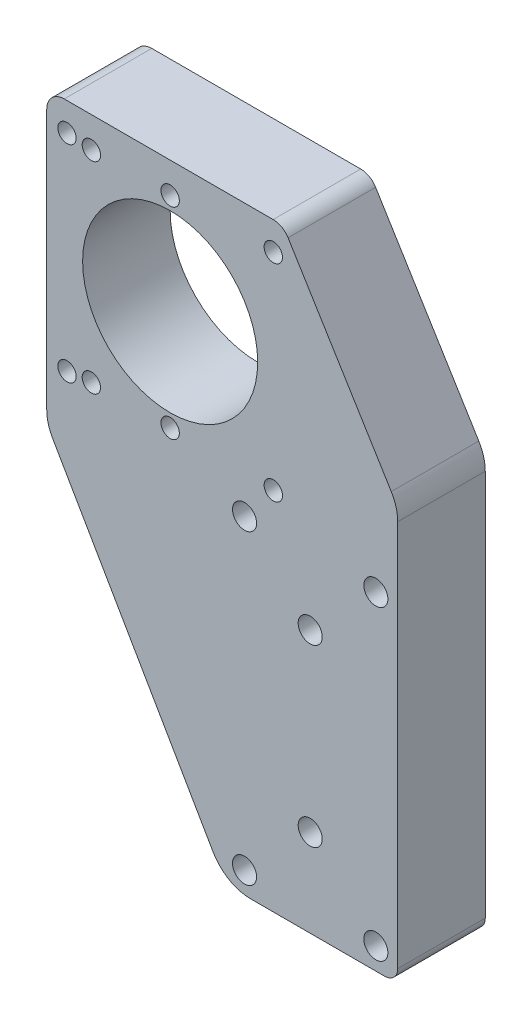
SolidWorks part; units mm, degrees
ref_plane "Front Plane" through (0, 0, 0) normal (0, 0, 1) x (1, 0, 0)
ref_plane "Top Plane" through (0, 0, 0) normal (0, 1, 0) x (1, 0, 0)
ref_plane "Right Plane" through (0, 0, 0) normal (1, 0, 0) x (0, 0, -1)
sketch "Sketch1" plane through (0, 0, 0) normal (0, 0, 1) x (1, 0, 0)
  line L0 (-130, 510) -> (13.8884, 510) construction
  line L1 (-170.2, 540.8246) -> (-129.3094, 470)
  line L2 (-116.2253, 607) -> (-90, 564.2553)
  line L15 (-90, 473) -> (-90, 564.2553)
  line L16 (-90, 473) -> (-90, 547) construction
  line L24 (-170.2, 540.8246) -> (-170.2, 607)
  line L25 (-170.2, 607) -> (-116.2253, 607)
  line L183 (-129.3094, 470) -> (-93, 470)
  arc A1 (-113.8, 602.2) -> (-116.8, 605.2) centre (-116.8, 602.2) ccw construction
  arc A13 (-90, 473) -> (-93, 470) centre (-93, 473) cw
extrude "Boss-Extrude1" add sketch "Sketch1" along normal blind 20
fillet "Fillet1" radius 10 3 edges at (-129.3094, 470, 10) (-170.2, 540.8246, 10) (-90, 564.2553, 10)
sketch "Sketch2" plane through (0, 0, 20) normal (0, 0, 1) x (1, 0, 0)
  circle A0 centre (-142, 577) radius 20
  point P2 (-142, 577)
  dimension "D1" = 40
extrude "Cut-Extrude1" cut sketch "Sketch2" against normal blind 20
hole_wizard "Tap Drill for M5 Tap1" positions "Sketch5" profile "Sketch6" hole size "M5" standard "ISO" end condition through all
sketch "Sketch5" plane through (0, 0, 0) normal (0, 0, -1) x (-1, 0, 0)
  line L1 (160, 600) -> (142, 600)
  line L2 (160, 600) -> (160, 554)
  line L3 (160, 554) -> (142, 554)
  line L4 (142, 600) -> (142, 554)
  circle A1 centre (160, 600) radius 2.1
  point P2 (160, 600)
  point P4 (142, 600)
  point P6 (142, 554)
  point P8 (160, 554)
  point P79 (160, 554)
  dimension "D1" = 18
  dimension "D2" = 46
  dimension "D3" = 46
  dimension "D4" = 18
sketch "Sketch6" plane through (-160, 600, 0) normal (1, 0, 0) x (0, 1, 0)
  line L0 (0, 0) -> (0, 20)
  line L1 (0, 20) -> (2.1, 20)
  line L2 (2.1, 20) -> (2.1, 0)
  line L5 (2.1, 0) -> (0, 0)
  line L11 (0, -6.35) -> (0, 107.95) construction
  dimension "Thru Hole Dia." = 4.2
  dimension "Thru Hole Depth" = 20
hole_wizard "M5 Clearance Hole1" positions "Sketch7" profile "Sketch8" hole size "M5" standard "ISO" end condition through all
sketch "Sketch7" plane through (0, 0, 20) normal (0, 0, 1) x (1, 0, 0)
  point P0 (-95, 545)
  point P2 (-125, 545)
  point P4 (-125, 475)
  point P6 (-95, 475)
  point P8 (-110, 490)
  point P10 (-110, 530)
sketch "Sketch8" plane through (-95, 545, 20) normal (1, 0, 0) x (0, -1, 0)
  line L0 (0, 0) -> (0, 20)
  line L1 (0, 20) -> (2.75, 20)
  line L2 (2.75, 20) -> (2.75, 0)
  line L5 (2.75, 0) -> (0, 0)
  line L11 (0, -6.35) -> (0, 107.95) construction
  dimension "Thru Hole Dia." = 5.5
  dimension "Thru Hole Depth" = 20
hole_wizard "Tap Drill for M5 Tap2" positions "Sketch9" profile "Sketch10" hole size "M5" standard "ISO" end condition through all
sketch "Sketch9" plane through (0, 0, 20) normal (0, 0, 1) x (1, 0, 0)
  point P0 (-165.57, 553.43)
  point P2 (-165.57, 600.57)
  point P4 (-118.43, 553.43)
  point P6 (-118.43, 600.57)
sketch "Sketch10" plane through (-165.57, 553.43, 20) normal (1, 0, 0) x (0, -1, 0)
  line L0 (0, 0) -> (0, 20)
  line L1 (0, 20) -> (2.1, 20)
  line L2 (2.1, 20) -> (2.1, 0)
  line L5 (2.1, 0) -> (0, 0)
  line L11 (0, -6.35) -> (0, 107.95) construction
  dimension "Thru Hole Dia." = 4.2
  dimension "Thru Hole Depth" = 20
fillet "Fillet2" radius 4 2 edges at (-116.2253, 607, 10) (-170.2, 607, 10)
